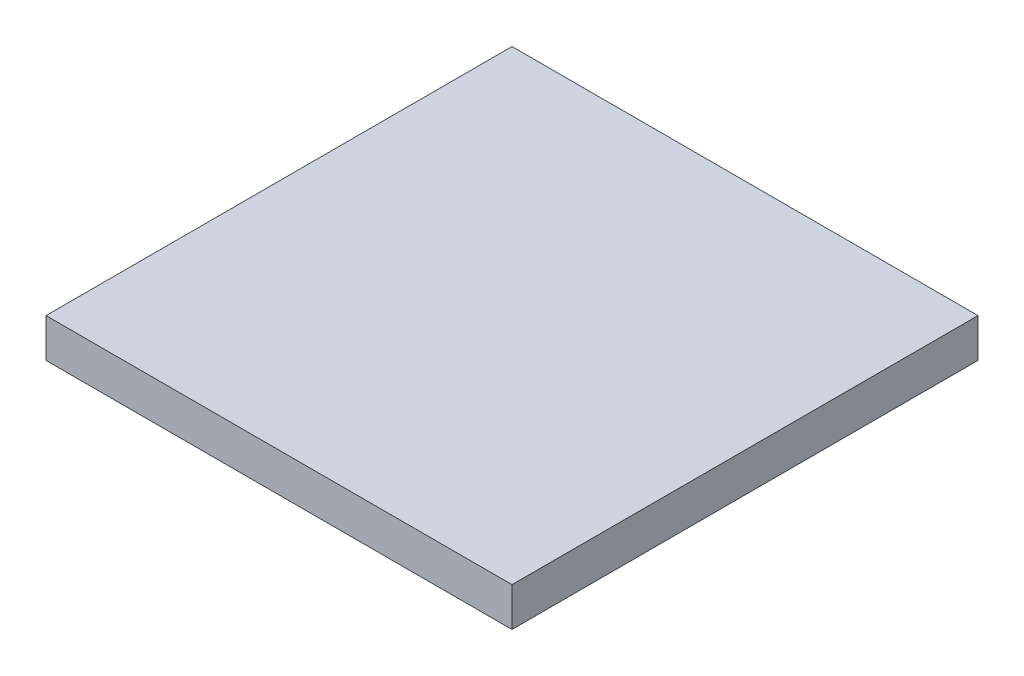
SolidWorks part; units mm, degrees
material "Ceramic Porcelain"
ref_plane "Front Plane" through (0, 0, 0) normal (0, 0, 1) x (1, 0, 0)
ref_plane "Top Plane" through (0, 0, 0) normal (0, 1, 0) x (1, 0, 0)
ref_plane "Right Plane" through (0, 0, 0) normal (1, 0, 0) x (0, 0, -1)
sketch "Sketch1" plane through (0, 0, 0) normal (0, 1, 0) x (1, 0, 0)
  line L1 (-19.05, 19.05) -> (19.05, 19.05)
  line L2 (-19.05, 19.05) -> (-19.05, -19.05)
  line L3 (-19.05, -19.05) -> (19.05, -19.05)
  line L4 (19.05, 19.05) -> (19.05, -19.05)
  point P4 (-19.05, 0)
  dimension "D1" = 38.1
  dimension "D2" = 38.1
  dimension "D3" = 19.05
  dimension "D4" = 19.05
extrude "Boss-Extrude1" add sketch "Sketch1" along normal blind 3.175
